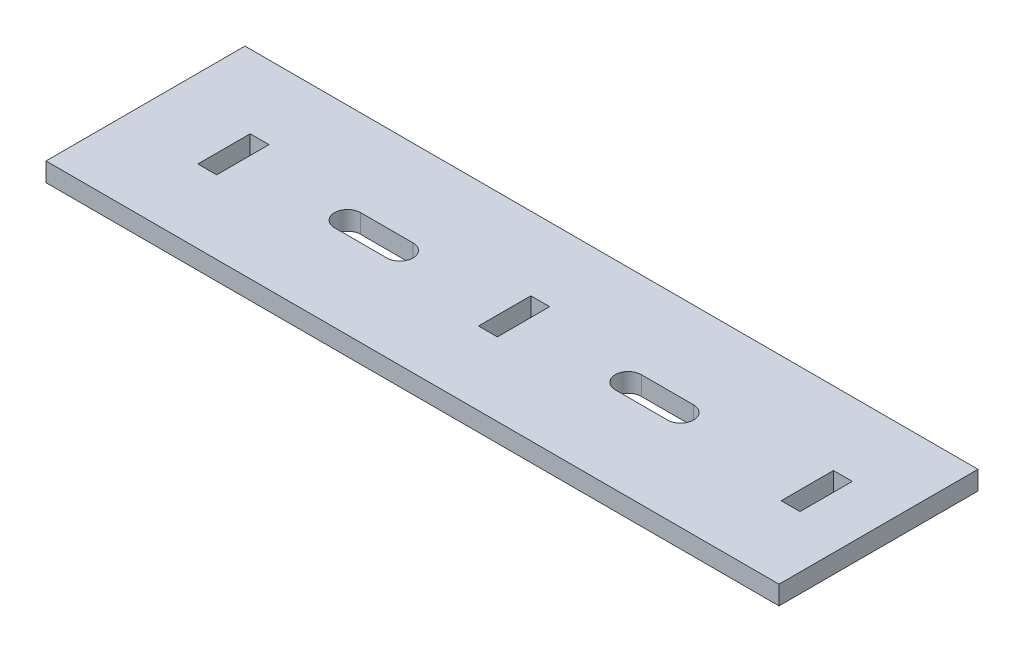
SolidWorks part; units mm, degrees
ref_plane "Front Plane" through (0, 0, 0) normal (0, 0, 1) x (1, 0, 0)
ref_plane "Top Plane" through (0, 0, 0) normal (0, 1, 0) x (1, 0, 0)
ref_plane "Right Plane" through (0, 0, 0) normal (1, 0, 0) x (0, 0, -1)
sketch "Sketch1" plane through (0, 0, 0) normal (0, 1, 0) x (1, 0, 0)
  line L1 (0, 0) -> (177.8, 0)
  line L2 (0, 0) -> (0, 48.26)
  line L3 (0, 48.26) -> (177.8, 48.26)
  line L4 (177.8, 0) -> (177.8, 48.26)
  line L5 (165.1, 17.78) -> (160.528, 17.78)
  line L6 (165.1, 17.78) -> (165.1, 30.48)
  line L7 (165.1, 30.48) -> (160.528, 30.48)
  line L8 (160.528, 17.78) -> (160.528, 30.48)
  line L9 (91.694, 17.78) -> (87.122, 17.78)
  line L10 (91.694, 17.78) -> (91.694, 30.48)
  line L11 (91.694, 30.48) -> (87.122, 30.48)
  line L12 (87.122, 17.78) -> (87.122, 30.48)
  line L13 (23.622, 17.78) -> (19.05, 17.78)
  line L14 (23.622, 17.78) -> (23.622, 30.48)
  line L15 (23.622, 30.48) -> (19.05, 30.48)
  line L16 (19.05, 17.78) -> (19.05, 30.48)
  point P17 (0, 24.13)
  point P18 (19.05, 24.13)
  dimension "D1" = 177.8
  dimension "D2" = 48.26
  dimension "D3" = 19.05
  dimension "D4" = 12.7
  dimension "D5" = 63.5
  dimension "D6" = 4.572
  dimension "D7" = 12.7
extrude "Boss-Extrude1" add sketch "Sketch1" along normal blind 4.572
sketch "Sketch2" plane through (0, 4.572, 0) normal (0, 1, 0) x (1, 0, 0)
  line L0 (177.8, 0) -> (177.8, 48.26) construction
  line L1 (49.022, 27.305) -> (61.722, 27.305)
  line L3 (49.022, 20.955) -> (61.722, 20.955)
  line L5 (117.094, 27.305) -> (129.794, 27.305)
  line L7 (117.094, 20.955) -> (129.794, 20.955)
  line L9 (87.122, 30.48) -> (87.122, 17.78) construction
  line L10 (91.694, 17.78) -> (91.694, 30.48) construction
  arc A0 (61.722, 20.955) -> (61.722, 27.305) centre (61.722, 24.13) ccw
  arc A1 (49.022, 27.305) -> (49.022, 20.955) centre (49.022, 24.13) ccw
  arc A2 (117.094, 27.305) -> (117.094, 20.955) centre (117.094, 24.13) ccw
  arc A3 (129.794, 20.955) -> (129.794, 27.305) centre (129.794, 24.13) ccw
  point P13 (177.8, 24.13)
  dimension "D1" = 6.35
  dimension "D2" = 12.7
  dimension "D3" = 25.4
  dimension "D4" = 25.4
extrude "Cut-Extrude1" cut sketch "Sketch2" against normal blind 5.08
